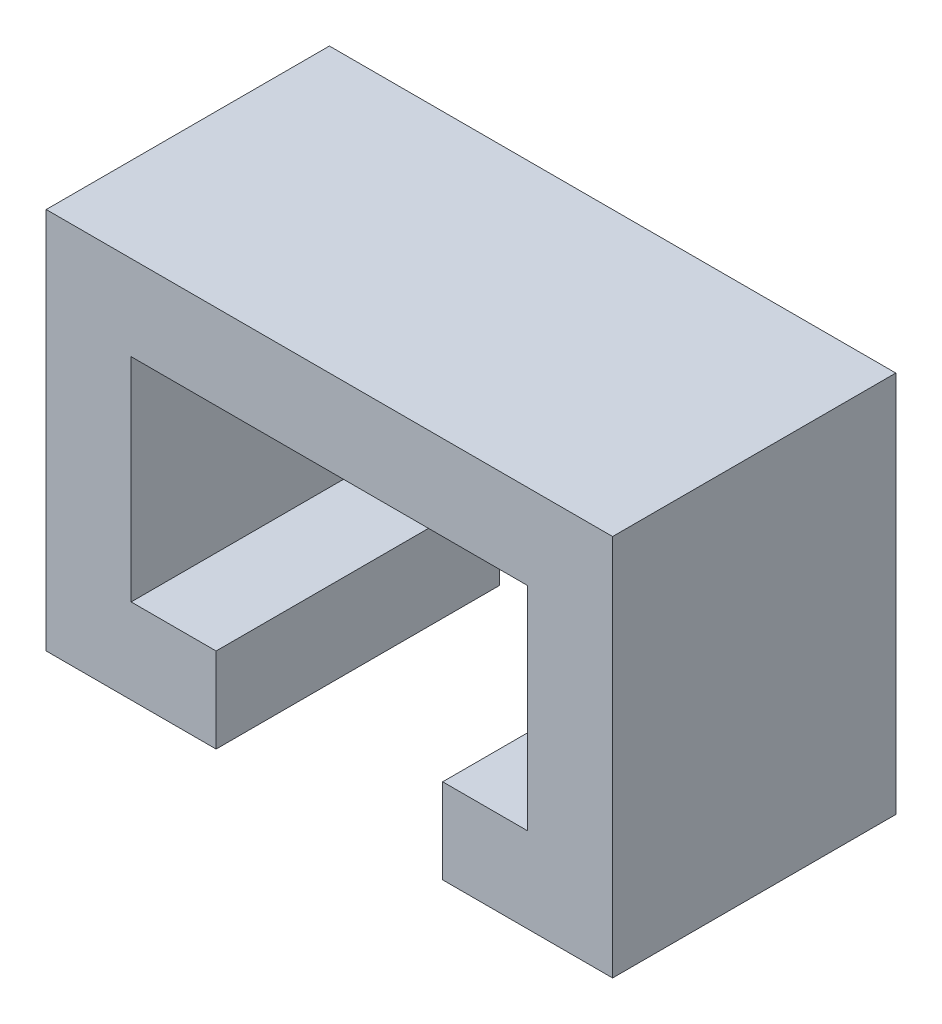
SolidWorks part; units mm, degrees
ref_plane "Piano frontale" through (0, 0, 0) normal (0, 0, 1) x (1, 0, 0)
ref_plane "Piano superiore" through (0, 0, 0) normal (0, 1, 0) x (1, 0, 0)
ref_plane "Piano destro" through (0, 0, 0) normal (1, 0, 0) x (0, 0, -1)
sketch "Schizzo2" plane through (0, 0, 0) normal (0, 0, 1) x (1, 0, 0)
  line L0 (-7, 0) -> (-7, 7.5)
  line L1 (-7, 7.5) -> (7, 7.5)
  line L2 (7, 7.5) -> (7, 0)
  line L3 (7, 0) -> (4, 0)
  line L4 (4, 0) -> (4, -3)
  line L5 (4, -3) -> (10, -3)
  line L6 (10, -3) -> (10, 10.5)
  line L7 (10, 10.5) -> (-10, 10.5)
  line L8 (-10, 10.5) -> (-10, -3)
  line L9 (-10, -3) -> (-4, -3)
  line L10 (-4, -3) -> (-4, 0)
  line L12 (-4, 0) -> (-7, 0)
  point P9 (0, 7.5)
  point P15 (0, 10.5)
  dimension "D1" = 14
  dimension "D2" = 7.5
  dimension "D3" = 3
  dimension "D4" = 3
  dimension "D5" = 3
  dimension "D6" = 3
extrude "Boss-Extrude1" add sketch "Schizzo2" along normal blind 10
